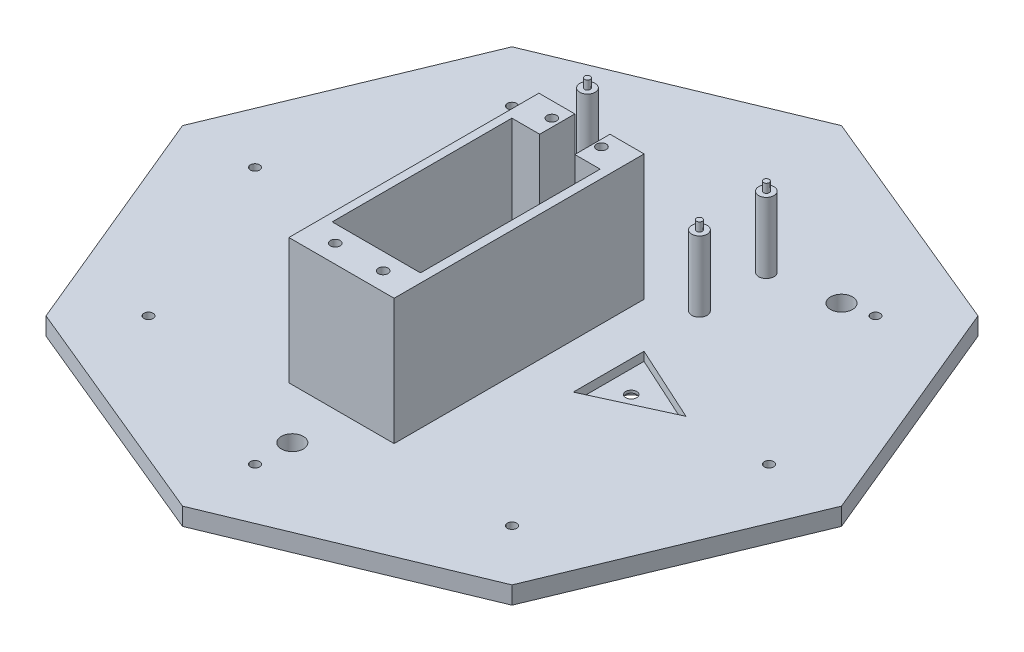
SolidWorks part; units mm, degrees
ref_plane "Ebene vorne" through (0, 0, 0) normal (0, 0, 1) x (1, 0, 0)
ref_plane "Ebene oben" through (0, 0, 0) normal (0, 1, 0) x (1, 0, 0)
ref_plane "Ebene rechts" through (0, 0, 0) normal (1, 0, 0) x (0, 0, -1)
sketch "Skizze2" plane through (0, 0, 0) normal (0, 1, 0) x (1, 0, 0)
  line L0 (-75, 0) -> (75, 0) construction
  line L1 (-55, 0) -> (55, 0) construction
  line L2 (0, -55) -> (0, 55) construction
  line L3 (-53.033, -53.033) -> (53.033, 53.033)
  line L4 (53.033, -53.033) -> (-53.033, 53.033)
  line L5 (-75, 0) -> (-53.033, 53.033)
  line L6 (-53.033, 53.033) -> (0, 75)
  line L7 (0, 75) -> (53.033, 53.033)
  line L8 (75, 0) -> (53.033, 53.033)
  line L9 (75, 0) -> (53.033, -53.033)
  line L10 (53.033, -53.033) -> (0, -75)
  line L11 (0, -75) -> (-53.033, -53.033)
  line L12 (-75, 0) -> (-53.033, -53.033)
  point P10 (0, 0)
  point P13 (0, 0)
  dimension "D1" = 150
  dimension "D2" = 75
  dimension "D3" = 150
  dimension "D4" = 150
  dimension "D5" = 45
  dimension "D6" = 45
  dimension "D7" = 75
  dimension "D8" = 75
extrude "Aufsatz-Linear austragen1" add sketch "Skizze2" along normal blind 3 and the other way blind 1 contours L7 L6 L4 L3 | L3 L0 L8 | L0 L4 L9 | L11 L10 L4 L3 | L5 L0 L4 | L0 L12 L3
sketch "Skizze5" plane through (0, 0, 0) normal (0, 1, 0) x (1, 0, 0)
  line L5 (53.033, -53.033) -> (-53.033, -53.033) construction
  line L6 (-53.033, 53.033) -> (53.033, 53.033) construction
  line L17 (-4, 18.307) -> (-4, 10.307)
  line L18 (-12.1859, -38.593) -> (11.7641, -38.593)
  line L19 (-12.1859, -38.593) -> (-12.1859, 18.307)
  line L20 (-12.1859, 18.307) -> (-4, 18.307)
  line L21 (11.7641, -38.593) -> (11.7641, 18.307)
  line L24 (-10.3359, -30.593) -> (9.7641, -30.593)
  line L25 (-10.3359, -30.593) -> (-10.3359, 10.307)
  line L26 (-10.3359, 10.307) -> (-4, 10.307)
  line L27 (9.7641, -30.593) -> (9.7641, 10.307)
  line L31 (4, 10.307) -> (4, 18.307)
  line L32 (0, -17.9575) -> (0, 17.9575) construction
  line L33 (4, 18.307) -> (11.7641, 18.307)
  line L34 (4, 10.307) -> (9.7641, 10.307)
  dimension "D2" = 8
  dimension "D3" = 14.44
  dimension "D4" = 106.066
  dimension "D7" = 20.1
  dimension "D8" = 40.9
  dimension "D9" = 2
  dimension "D10" = 8
  dimension "D11" = 4
  dimension "D12" = 4
extrude "Aufsatz-Linear austragen3" add sketch "Skizze5" along normal blind 31.65
sketch "Skizze7" plane through (0, 3, 0) normal (0, 1, 0) x (1, 0, 0)
  line L0 (-17.9575, 0) -> (17.9575, 0) construction
  line L5 (-35, -40) -> (33.3537, 38.1186) construction
  line L6 (-33.3537, 38.1186) -> (35, -40) construction
  circle A0 centre (35, 40) radius 2.5
  circle A1 centre (-35, 40) radius 2.5
  circle A2 centre (0, -50) radius 2.5
  point P0 (0, 0)
  dimension "D3" = 5
  dimension "D4" = 5
  dimension "D5" = 5
  dimension "D6" = 50
  dimension "D1" = 80
  dimension "D2" = 70
extrude "Schnitt-Linear austragen2" cut sketch "Skizze7" against normal through all
sketch "Skizze8" plane through (0, 3, 0) normal (0, 1, 0) x (1, 0, 0)
  line L0 (-75, 0) -> (75, 0) construction
  line L7 (-22, 8.05) -> (-22, -8.05)
  line L8 (-40.3423, -0.3395) -> (-22, -8.05) construction
  line L9 (-40.3423, 0.3395) -> (-22, 8.05) construction
  line L12 (22, 8.05) -> (22, -8.05)
  line L15 (22, 8.05) -> (36.597, 1.9139) construction
  line L16 (22, -8.05) -> (40.3423, -0.3395) construction
  line L18 (0, -17.9575) -> (0, 17.9575) construction
  line L19 (-39.6, 0) -> (-22, -8.05)
  line L21 (-22, 8.05) -> (-39.6, 0)
  line L22 (22, -8.05) -> (39.6, 0)
  line L23 (39.6, 0) -> (22, 8.05)
  line L24 (22, -8.05) -> (22, 8.05)
  point P2 (-41.15, 0)
  point P7 (41.15, 0)
  dimension "D1" = 22
  dimension "D2" = 22
  dimension "D3" = 16.1
  dimension "D4" = 17.6
  dimension "D5" = 17.6
  dimension "D6" = 16.1
extrude "Schnitt-Linear austragen6" cut sketch "Skizze8" against normal blind 2 contours L7 L21 L19 | L22 L23 L12
sketch "Skizze10" plane through (0, 1, 0) normal (0, 1, 0) x (1, 0, 0)
  line L0 (22, 8.05) -> (22, -8.05) construction
  line L1 (-27.7762, 3.1696) -> (3.5706, -29.5966) construction
  line L2 (-22, 8.05) -> (-22, -8.05) construction
  line L7 (41.9977, 0.05) -> (22.7023, 0.05) construction
  circle A0 centre (-27.0878, -51.7809) radius 1.25
  circle A1 centre (27.09, 0.05) radius 1.25
  dimension "D1" = 2.5
  dimension "D2" = 0
  dimension "D3" = 37.4889
  dimension "D4" = 5.09
  dimension "D5" = 5.0878
extrude "Schnitt-Linear austragen7" cut sketch "Skizze10" against normal through all
sketch "Skizze11" plane through (0, -1, 0) normal (0, -1, 0) x (1, 0, 0)
  circle A0 centre (-27.0878, 51.7809) radius 2.75
  circle A1 centre (27.09, -0.05) radius 2.75
  dimension "D1" = 5.5
  dimension "D2" = 5.5
extrude "Schnitt-Linear austragen8" cut sketch "Skizze11" against normal blind 1.4
sketch "Skizze14" plane through (0, 3, 0) normal (0, 1, 0) x (1, 0, 0)
  line L0 (0, 0) -> (-51.0988, 51.0988) construction
  line L1 (-51.0988, 51.0988) -> (0, 0) construction
  line L2 (0, 0) -> (44.6211, 44.6211) construction
  line L3 (44.6211, 44.6211) -> (0, 0) construction
  line L4 (0, 0) -> (42.9287, -42.9287) construction
  line L5 (42.9287, -42.9287) -> (0, 0) construction
  line L6 (0, 0) -> (-43.4336, -43.4336) construction
  circle A1 centre (-58.5, 0) radius 1.05
  circle A3 centre (-41.3657, 41.3657) radius 1.05
  circle A4 centre (41.3657, 41.3657) radius 1.05
  circle A5 centre (58.5, 0) radius 1.05
  circle A6 centre (41.3657, -41.3657) radius 1.05
  circle A7 centre (-41.3657, -41.3657) radius 1.05
  circle A8 centre (0, -58.5) radius 1.05
  dimension "D2" = 2.1
  dimension "D3" = 2.1
  dimension "D4" = 2.1
  dimension "D5" = 2.1
  dimension "D6" = 2.1
  dimension "D7" = 2.1
  dimension "D8" = 2.1
extrude "Schnitt-Linear austragen9" cut sketch "Skizze14" against normal blind 10
sketch "Skizze15" plane through (0, 3, 0) normal (0, 1, 0) x (1, 0, 0)
  line L0 (0, -17.9575) -> (0, 17.9575) construction
  line L1 (-20.36, 22.307) -> (20.36, 22.307)
  line L2 (-20.36, 22.307) -> (-20.36, 37.537)
  line L3 (-20.36, 37.537) -> (20.36, 37.537)
  line L4 (20.36, 22.307) -> (20.36, 37.537)
  line L5 (-20.36, 22.307) -> (20.36, 37.537) construction
  line L6 (-20.36, 37.537) -> (20.36, 22.307) construction
  line L7 (4, 18.307) -> (11.7641, 18.307) construction
  circle A0 centre (-20.36, 37.537) radius 1.75
  circle A1 centre (-20.36, 22.307) radius 1.75
  circle A2 centre (20.36, 22.307) radius 1.75
  circle A3 centre (20.36, 37.537) radius 1.75
  point P0 (0, 29.922)
  dimension "D4" = 3.5
  dimension "D5" = 3.5
  dimension "D6" = 3.5
  dimension "D7" = 3.5
  dimension "D1" = 40.72
  dimension "D2" = 15.23
  dimension "D3" = 4
extrude "Aufsatz-Linear austragen4" add sketch "Skizze15" along normal blind 16 contours L4 A3 L3 | L3 A3 L4 | L2 A1 L1 | L1 A1 L2 | L2 A0 L3 | L3 A0 L2 | A2
sketch "Skizze16" plane through (0, 19, 0) normal (0, 1, 0) x (1, 0, 0)
  circle A0 centre (20.36, 22.307) radius 0.65
  circle A1 centre (20.36, 37.537) radius 0.65
  circle A2 centre (-20.36, 37.537) radius 0.65
  circle A3 centre (-20.36, 22.307) radius 0.65
  dimension "D1" = 1.3
  dimension "D2" = 1.3
  dimension "D3" = 1.3
  dimension "D4" = 1.3
extrude "Aufsatz-Linear austragen5" add sketch "Skizze16" along normal blind 2
sketch "Skizze18" plane through (0, 31.65, 0) normal (0, 1, 0) x (1, 0, 0)
  line L0 (4, 18.307) -> (4, 10.307) construction
  circle A0 centre (-5.7859, 14.857) radius 1.1
  circle A1 centre (5.5, 14.857) radius 1.1
  circle A2 centre (5.1141, -34.443) radius 1.1
  circle A3 centre (-5.7859, -34.443) radius 1.1
  dimension "D1" = 2.2
  dimension "D2" = 2.2
  dimension "D3" = 2.2
  dimension "D4" = 2.2
  dimension "D5" = 1.5
extrude "Schnitt-Linear austragen10" cut sketch "Skizze18" against normal blind 13
